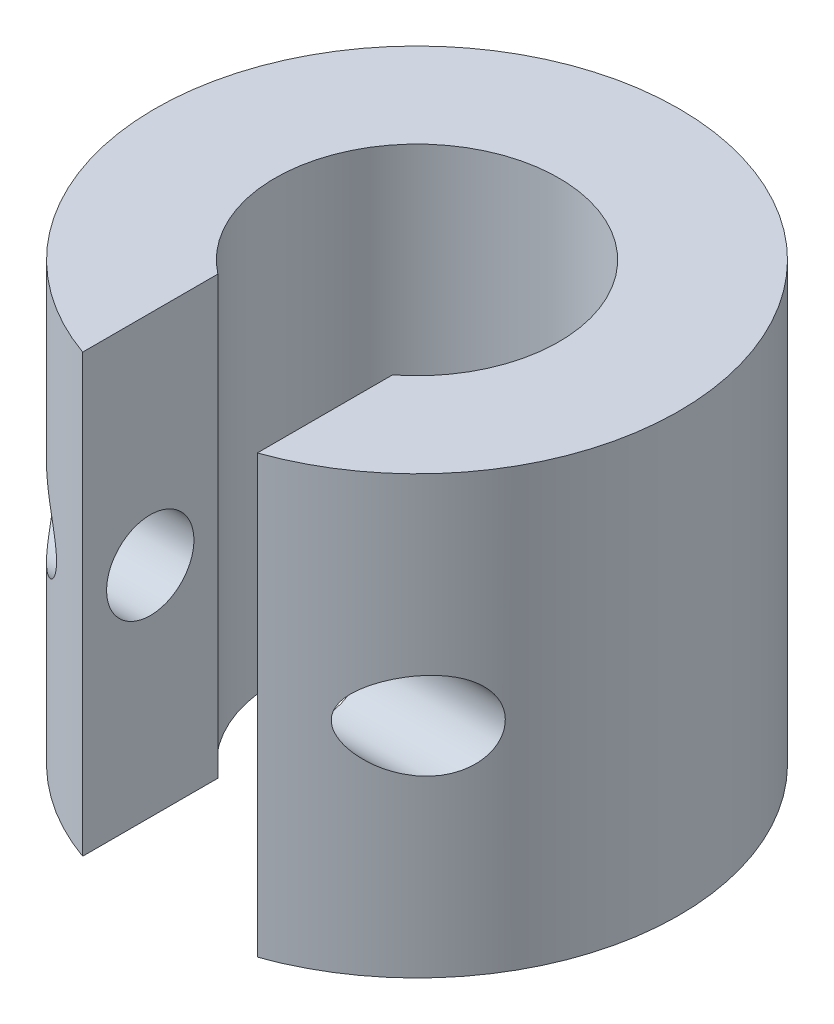
SolidWorks part; units mm, degrees
ref_plane "Front" through (0, 0, 0) normal (0, 0, 1) x (1, 0, 0)
ref_plane "Top" through (0, 0, 0) normal (0, 1, 0) x (1, 0, 0)
ref_plane "Right" through (0, 0, 0) normal (1, 0, 0) x (0, 0, -1)
other "Configuration Table"
sketch "Sketch1" plane through (0, 0, 0) normal (0, 1, 0) x (1, 0, 0)
  line L0 (-3.862, 4.6384) -> (-3.862, 1.8884)
  line L1 (-3.862, 1.8884) -> (-1.862, 1.8884)
  line L2 (-1.862, 1.8884) -> (-1.862, 5.3266)
  line L3 (-3.862, 1.8884) -> (-5.862, 1.8884)
  line L4 (-5.862, 1.8884) -> (-5.862, 5.3266)
  circle A0 centre (-3.862, 7.8884) radius 3.25
  circle A1 centre (-3.862, 7.8884) radius 6
  dimension "D1" = 6.5
  dimension "D2" = 12
  dimension "D3" = 2
  dimension "D4" = 2
extrude "Boss-Extrude1" add sketch "Sketch1" along normal blind 10 contours L2 A1 L4 A0
sketch "Sketch2" plane through (-5.862, 0, 0) normal (1, 0, 0) x (0, 0, -1)
  line L1 (3.7791, 10) -> (3.7791, 0) construction
  line L2 (2.2315, 10) -> (5.3266, 10) construction
  line L3 (2.2315, 0) -> (5.3266, 0) construction
  line L4 (2.2315, 5) -> (5.3266, 5) construction
  line L5 (2.2315, 10) -> (2.2315, 0) construction
  line L6 (5.3266, 10) -> (5.3266, 0) construction
  circle A1 centre (3.7791, 5) radius 1
  dimension "D1" = 2
extrude "Cut-Extrude1" cut sketch "Sketch2" against normal blind 10 and the other way blind 10
